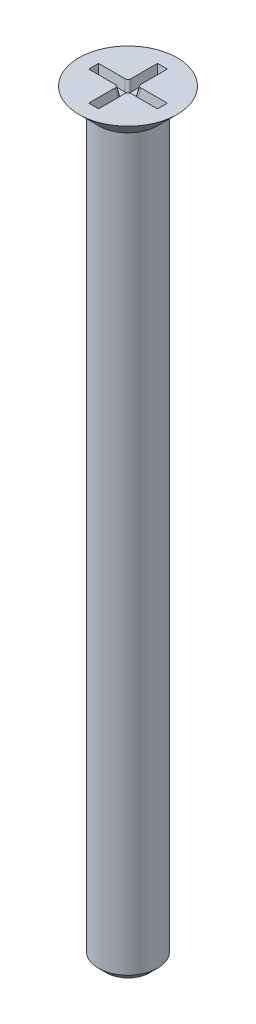
SolidWorks part; units mm, degrees
ref_plane "前视基准面" through (0, 0, 0) normal (0, 0, 1) x (1, 0, 0)
ref_plane "上视基准面" through (0, 0, 0) normal (0, 1, 0) x (1, 0, 0)
ref_plane "右视基准面" through (0, 0, 0) normal (1, 0, 0) x (0, 0, -1)
other "Configuration Table"
sketch "草图1" plane through (0, 0, 0) normal (0, 0, 1) x (1, 0, 0)
  line L0 (0, 0) -> (5, 0)
  line L1 (5, 0) -> (3, -2)
  line L2 (3, -2) -> (0, -2)
  line L3 (0, -2) -> (0, 0)
  dimension "D1" = 5
  dimension "D2" = 2
  dimension "D3" = 3
revolve "旋转1" add sketch "草图1" angle 360 about L3
sketch "草图2" plane through (0, -2, 0) normal (0, -1, 0) x (1, 0, 0)
  circle A1 centre (0, 0) radius 3
  circle A2 centre (0, 0) radius 3
  dimension "D1" = 0
extrude "凸台-拉伸1" add sketch "草图2" along normal blind 75
cosmetic thread "装饰螺纹线1" parameters "D2"=4.917
chamfer "倒角1" distance 0.8 angle 45 1 edges at (0, -77, -3)
sketch "草图3" plane through (0, 0, 0) normal (0, 1, 0) x (1, 0, 0)
  line L1 (-3.5, -0.5) -> (3.5, -0.5)
  line L2 (-3.5, -0.5) -> (-3.5, 0.5)
  line L3 (-3.5, 0.5) -> (3.5, 0.5)
  line L4 (3.5, -0.5) -> (3.5, 0.5)
  line L5 (-3.5, -0.5) -> (3.5, 0.5) construction
  line L6 (-3.5, 0.5) -> (3.5, -0.5) construction
  line L7 (-0.5, 3.5) -> (0.5, 3.5)
  line L8 (-0.5, 3.5) -> (-0.5, -3.5)
  line L9 (-0.5, -3.5) -> (0.5, -3.5)
  line L10 (0.5, 3.5) -> (0.5, -3.5)
  line L11 (-0.5, 3.5) -> (0.5, -3.5) construction
  line L12 (-0.5, -3.5) -> (0.5, 3.5) construction
  point P0 (0, 0)
  point P6 (0, 0)
  dimension "D1" = 1
  dimension "D2" = 1
  dimension "D3" = 7
  dimension "D4" = 7
extrude "切除-拉伸1" cut sketch "草图3" against normal blind 1 draft 10 contours L3 L10 L1 L4 | L10 L7 L8 L3 | L8 L3 L2 L1 | L10 L3 L8 L1 | L10 L1 L8 L9
fillet "圆角1" radius 0.3 4 edges at (-0.4118, -0.5, -0.4118) (0.4118, -0.5, -0.4118) (-0.4118, -0.5, 0.4118) (0.4118, -0.5, 0.4118)
